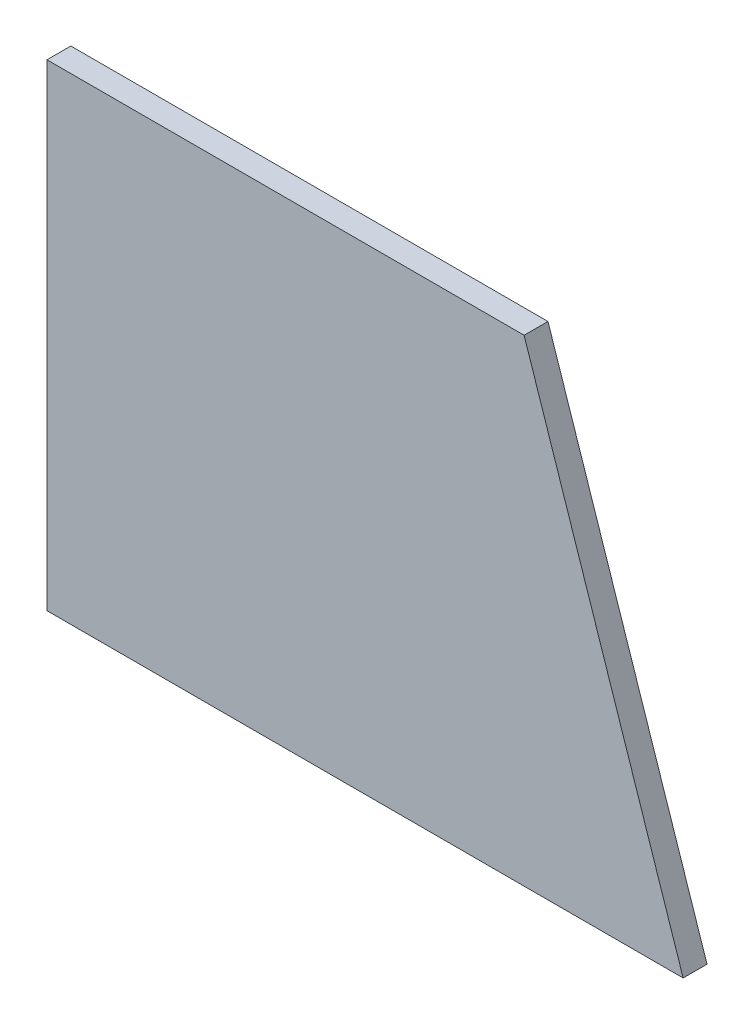
SolidWorks part; units mm, degrees
ref_plane "Front Plane" through (0, 0, 0) normal (0, 0, 1) x (1, 0, 0)
ref_plane "Top Plane" through (0, 0, 0) normal (0, 1, 0) x (1, 0, 0)
ref_plane "Right Plane" through (0, 0, 0) normal (1, 0, 0) x (0, 0, -1)
sketch "Sketch1" plane through (0, 0, 0) normal (0, 0, 1) x (1, 0, 0)
  line L4 (-0.2736, -0.2799) -> (-0.2736, 0.3201)
  line L5 (-0.3029, 0.3544) -> (0.2649, -0.3099) construction
  line L6 (-0.3029, -0.3099) -> (0.3463, 0.3544) construction
  line L8 (-0.2736, 0.3201) -> (0.3264, 0.3201)
  line L9 (0.3264, 0.3201) -> (0.5264, -0.2799)
  line L10 (0.5264, -0.2799) -> (-0.2736, -0.2799)
  point P0 (0, 0)
  point P6 (0.5797, -0.3099)
  point P12 (0, 0)
  dimension "D1" = 0.6
  dimension "D2" = 0.8
  dimension "D3" = 0.6
extrude "Boss-Extrude3" add sketch "Sketch1" along normal mid plane 0.03
